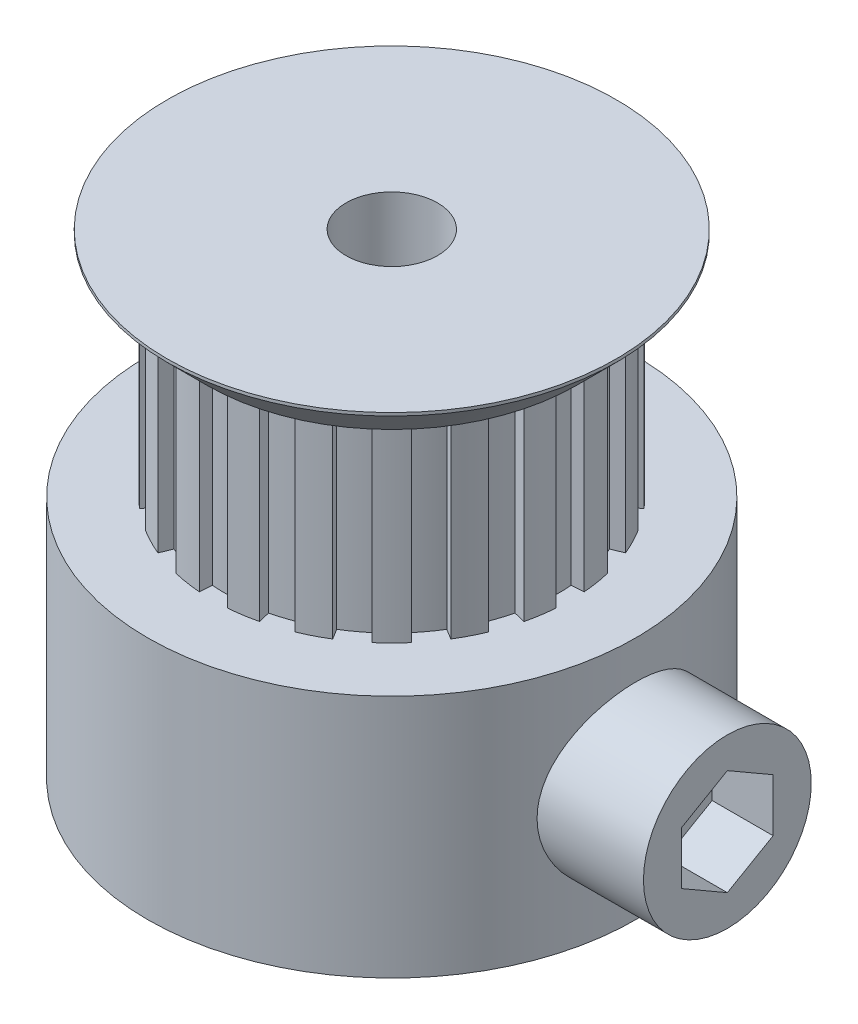
SolidWorks part; units mm, degrees
ref_plane "Front Plane" through (0, 0, 0) normal (0, 0, 1) x (1, 0, 0)
ref_plane "Top Plane" through (0, 0, 0) normal (0, 1, 0) x (1, 0, 0)
ref_plane "Right Plane" through (0, 0, 0) normal (1, 0, 0) x (0, 0, -1)
sketch "Sketch1" plane through (0, 0, 0) normal (0, 1, 0) x (1, 0, 0)
  circle A0 centre (0, 0) radius 8
  dimension "D1" = 16
extrude "Boss-Extrude1" add sketch "Sketch1" along normal blind 8
sketch "Sketch2" plane through (0, 8, 0) normal (0, 1, 0) x (1, 0, 0)
  circle A0 centre (0, 0) radius 5.865
  dimension "D1" = 11.73
extrude "Boss-Extrude2" add sketch "Sketch2" along normal blind 6.2
sketch "Sketch6" plane through (0, 14.2, 0) normal (0, 1, 0) x (1, 0, 0)
  line L0 (0, 0) -> (0, 5.865) construction
  line L1 (-0.4602, 5.8469) -> (0, 0) construction
  line L2 (0.4602, 5.8469) -> (0, 0) construction
  line L3 (-0.4602, 5.8469) -> (-0.4288, 5.4482)
  line L4 (0.4602, 5.8469) -> (0.4288, 5.4482)
  line L5 (2.2444, 5.4186) -> (2.0914, 5.049)
  line L6 (1.3692, 5.7029) -> (1.2758, 5.314)
  line L7 (3.809, 4.4598) -> (3.5492, 4.1556)
  line L8 (3.0645, 5.0007) -> (2.8555, 4.6597)
  line L9 (5.0007, 3.0645) -> (4.6597, 2.8555)
  line L10 (4.4598, 3.809) -> (4.1556, 3.5492)
  line L11 (5.7029, 1.3692) -> (5.314, 1.2758)
  line L12 (5.4186, 2.2444) -> (5.049, 2.0914)
  line L13 (5.8469, -0.4602) -> (5.4482, -0.4288)
  line L14 (5.8469, 0.4602) -> (5.4482, 0.4288)
  line L15 (5.4186, -2.2444) -> (5.049, -2.0914)
  line L16 (5.7029, -1.3692) -> (5.314, -1.2758)
  line L17 (4.4598, -3.809) -> (4.1556, -3.5492)
  line L18 (5.0007, -3.0645) -> (4.6597, -2.8555)
  line L19 (3.0645, -5.0007) -> (2.8555, -4.6597)
  line L20 (3.809, -4.4598) -> (3.5492, -4.1556)
  line L21 (1.3692, -5.7029) -> (1.2758, -5.314)
  line L22 (2.2444, -5.4186) -> (2.0914, -5.049)
  line L23 (-0.4602, -5.8469) -> (-0.4288, -5.4482)
  line L24 (0.4602, -5.8469) -> (0.4288, -5.4482)
  line L25 (-2.2444, -5.4186) -> (-2.0914, -5.049)
  line L26 (-1.3692, -5.7029) -> (-1.2758, -5.314)
  line L27 (-3.809, -4.4598) -> (-3.5492, -4.1556)
  line L28 (-3.0645, -5.0007) -> (-2.8555, -4.6597)
  line L29 (-5.0007, -3.0645) -> (-4.6597, -2.8555)
  line L30 (-4.4598, -3.809) -> (-4.1556, -3.5492)
  line L31 (-5.7029, -1.3692) -> (-5.314, -1.2758)
  line L32 (-5.4186, -2.2444) -> (-5.049, -2.0914)
  line L33 (-5.8469, 0.4602) -> (-5.4482, 0.4288)
  line L34 (-5.8469, -0.4602) -> (-5.4482, -0.4288)
  line L35 (-5.4186, 2.2444) -> (-5.049, 2.0914)
  line L36 (-5.7029, 1.3692) -> (-5.314, 1.2758)
  line L37 (-4.4598, 3.809) -> (-4.1556, 3.5492)
  line L38 (-5.0007, 3.0645) -> (-4.6597, 2.8555)
  line L39 (-3.0645, 5.0007) -> (-2.8555, 4.6597)
  line L40 (-3.809, 4.4598) -> (-3.5492, 4.1556)
  line L41 (-1.3692, 5.7029) -> (-1.2758, 5.314)
  line L42 (-2.2444, 5.4186) -> (-2.0914, 5.049)
  circle A0 centre (0, 0) radius 5.865 construction
  circle A1 centre (0, 0) radius 5.865 construction
  arc A2 (-0.4602, 5.8469) -> (0.4602, 5.8469) centre (0, 0) cw
  circle A3 centre (0, 0) radius 5.865 construction
  arc A4 (-0.4288, 5.4482) -> (0.4288, 5.4482) centre (0, 0) cw
  arc A5 (1.2758, 5.314) -> (2.0914, 5.049) centre (0, 0) cw
  arc A6 (1.3692, 5.7029) -> (2.2444, 5.4186) centre (0, 0) cw
  arc A7 (2.8555, 4.6597) -> (3.5492, 4.1556) centre (0, 0) cw
  arc A8 (3.0645, 5.0007) -> (3.809, 4.4598) centre (0, 0) cw
  arc A9 (4.1556, 3.5492) -> (4.6597, 2.8555) centre (0, 0) cw
  arc A10 (4.4598, 3.809) -> (5.0007, 3.0645) centre (0, 0) cw
  arc A11 (5.049, 2.0914) -> (5.314, 1.2758) centre (0, 0) cw
  arc A12 (5.4186, 2.2444) -> (5.7029, 1.3692) centre (0, 0) cw
  arc A13 (5.4482, 0.4288) -> (5.4482, -0.4288) centre (0, 0) cw
  arc A14 (5.8469, 0.4602) -> (5.8469, -0.4602) centre (0, 0) cw
  arc A15 (5.314, -1.2758) -> (5.049, -2.0914) centre (0, 0) cw
  arc A16 (5.7029, -1.3692) -> (5.4186, -2.2444) centre (0, 0) cw
  arc A17 (4.6597, -2.8555) -> (4.1556, -3.5492) centre (0, 0) cw
  arc A18 (5.0007, -3.0645) -> (4.4598, -3.809) centre (0, 0) cw
  arc A19 (3.5492, -4.1556) -> (2.8555, -4.6597) centre (0, 0) cw
  arc A20 (3.809, -4.4598) -> (3.0645, -5.0007) centre (0, 0) cw
  arc A21 (2.0914, -5.049) -> (1.2758, -5.314) centre (0, 0) cw
  arc A22 (2.2444, -5.4186) -> (1.3692, -5.7029) centre (0, 0) cw
  arc A23 (0.4288, -5.4482) -> (-0.4288, -5.4482) centre (0, 0) cw
  arc A24 (0.4602, -5.8469) -> (-0.4602, -5.8469) centre (0, 0) cw
  arc A25 (-1.2758, -5.314) -> (-2.0914, -5.049) centre (0, 0) cw
  arc A26 (-1.3692, -5.7029) -> (-2.2444, -5.4186) centre (0, 0) cw
  arc A27 (-2.8555, -4.6597) -> (-3.5492, -4.1556) centre (0, 0) cw
  arc A28 (-3.0645, -5.0007) -> (-3.809, -4.4598) centre (0, 0) cw
  arc A29 (-4.1556, -3.5492) -> (-4.6597, -2.8555) centre (0, 0) cw
  arc A30 (-4.4598, -3.809) -> (-5.0007, -3.0645) centre (0, 0) cw
  arc A31 (-5.049, -2.0914) -> (-5.314, -1.2758) centre (0, 0) cw
  arc A32 (-5.4186, -2.2444) -> (-5.7029, -1.3692) centre (0, 0) cw
  arc A33 (-5.4482, -0.4288) -> (-5.4482, 0.4288) centre (0, 0) cw
  arc A34 (-5.8469, -0.4602) -> (-5.8469, 0.4602) centre (0, 0) cw
  arc A35 (-5.314, 1.2758) -> (-5.049, 2.0914) centre (0, 0) cw
  arc A36 (-5.7029, 1.3692) -> (-5.4186, 2.2444) centre (0, 0) cw
  arc A37 (-4.6597, 2.8555) -> (-4.1556, 3.5492) centre (0, 0) cw
  arc A38 (-5.0007, 3.0645) -> (-4.4598, 3.809) centre (0, 0) cw
  arc A39 (-3.5492, 4.1556) -> (-2.8555, 4.6597) centre (0, 0) cw
  arc A40 (-3.809, 4.4598) -> (-3.0645, 5.0007) centre (0, 0) cw
  arc A41 (-2.0914, 5.049) -> (-1.2758, 5.314) centre (0, 0) cw
  arc A42 (-2.2444, 5.4186) -> (-1.3692, 5.7029) centre (0, 0) cw
  point P11 (0, 5.465)
  point P73 (0, 0)
  dimension "D1" = 0.4
  dimension "D2" = 9
  dimension "D3" = 20
extrude "Cut-Extrude2" cut sketch "Sketch6" against normal up to surface (6.2 mm away) up to face at (0, 8, 5.865)
sketch "Sketch3" plane through (0, 14.2, 0) normal (0, 1, 0) x (1, 0, 0)
  circle A0 centre (0, 0) radius 7.36
  dimension "D1" = 14.72
extrude "Boss-Extrude3" add sketch "Sketch3" along normal blind 1.4
chamfer "Chamfer1" distance 1.3 angle 45 1 edges at (0, 14.2, 7.36)
sketch "Sketch4" plane through (0, 0, 0) normal (1, 0, 0) x (0, 0, -1)
  line L0 (0, 8) -> (0, 0) construction
  line L1 (8, 8) -> (-8, 8) construction
  circle A0 centre (0, 4) radius 2.75
  point P8 (0, 4)
  dimension "D1" = 5.5
extrude "Boss-Extrude4" add sketch "Sketch4" along normal blind 11
sketch "Sketch5" plane through (11, 0, 0) normal (1, 0, 0) x (0, 0, -1)
  line L1 (0, 2.2679) -> (1.5, 3.134)
  line L2 (1.5, 3.134) -> (1.5, 4.866)
  line L3 (1.5, 4.866) -> (0, 5.7321)
  line L4 (0, 5.7321) -> (-1.5, 4.866)
  line L5 (-1.5, 4.866) -> (-1.5, 3.134)
  line L6 (-1.5, 3.134) -> (0, 2.2679)
  circle A0 centre (0, 4) radius 1.5 construction
  dimension "D1" = 3
extrude "Cut-Extrude1" cut sketch "Sketch5" against normal blind 2
sketch "Sketch7" plane through (0, 0, 0) normal (0, -1, 0) x (1, 0, 0)
  circle A0 centre (0, 0) radius 1.5
  dimension "D1" = 3
extrude "Cut-Extrude3" cut sketch "Sketch7" against normal through all
